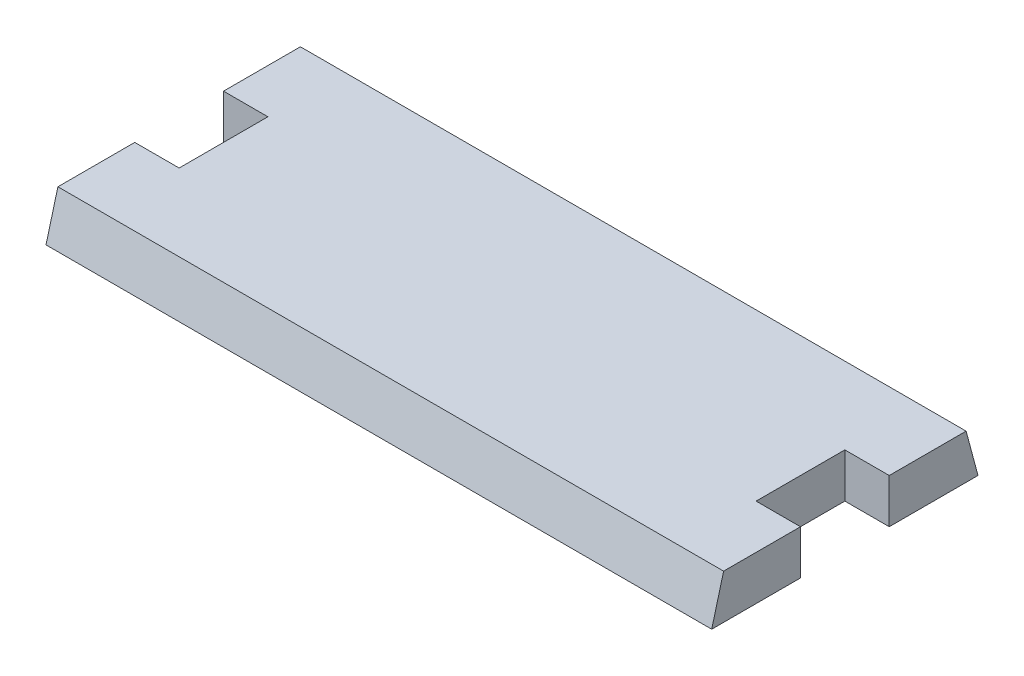
SolidWorks part; units mm, degrees
ref_plane "Front Plane" through (0, 0, 0) normal (0, 0, 1) x (1, 0, 0)
ref_plane "Top Plane" through (0, 0, 0) normal (0, 1, 0) x (1, 0, 0)
ref_plane "Right Plane" through (0, 0, 0) normal (1, 0, 0) x (0, 0, -1)
sketch "Sketch1" plane through (0, 0, 0) normal (0, 1, 0) x (1, 0, 0)
  line L0 (0, 38.7015) -> (0, -46.796) construction
  line L1 (-75, 30) -> (75, 30)
  line L2 (-75, 30) -> (-75, 10)
  line L3 (-75, -30) -> (75, -30)
  line L4 (75, 30) -> (75, 10)
  line L5 (-75, 30) -> (75, -30) construction
  line L6 (-75, -30) -> (75, 30) construction
  line L7 (75, 10) -> (65, 10)
  line L9 (75, -10) -> (65, -10)
  line L10 (65, 10) -> (65, -10)
  line L11 (-75, 10) -> (-65, 10)
  line L12 (-75, -10) -> (-65, -10)
  line L13 (-65, 10) -> (-65, -10)
  line L14 (-75, -10) -> (-75, -30)
  line L15 (75, -10) -> (75, -30)
  point P0 (0, 0)
  dimension "D1" = 150
  dimension "D2" = 60
  dimension "D3" = 10
  dimension "D4" = 20
  dimension "D5" = 20
extrude "Boss-Extrude1" add sketch "Sketch1" along normal blind 10
draft "Draft1" type of draft neutral plane draft angle 15 faces to draft 2 face at (0, 5, -30) face at (0, 5, 30) neutral plane through (0, 0, 0) neutral plane normal (0, -1, 0) reverse direction yes parameters "D1"=15
